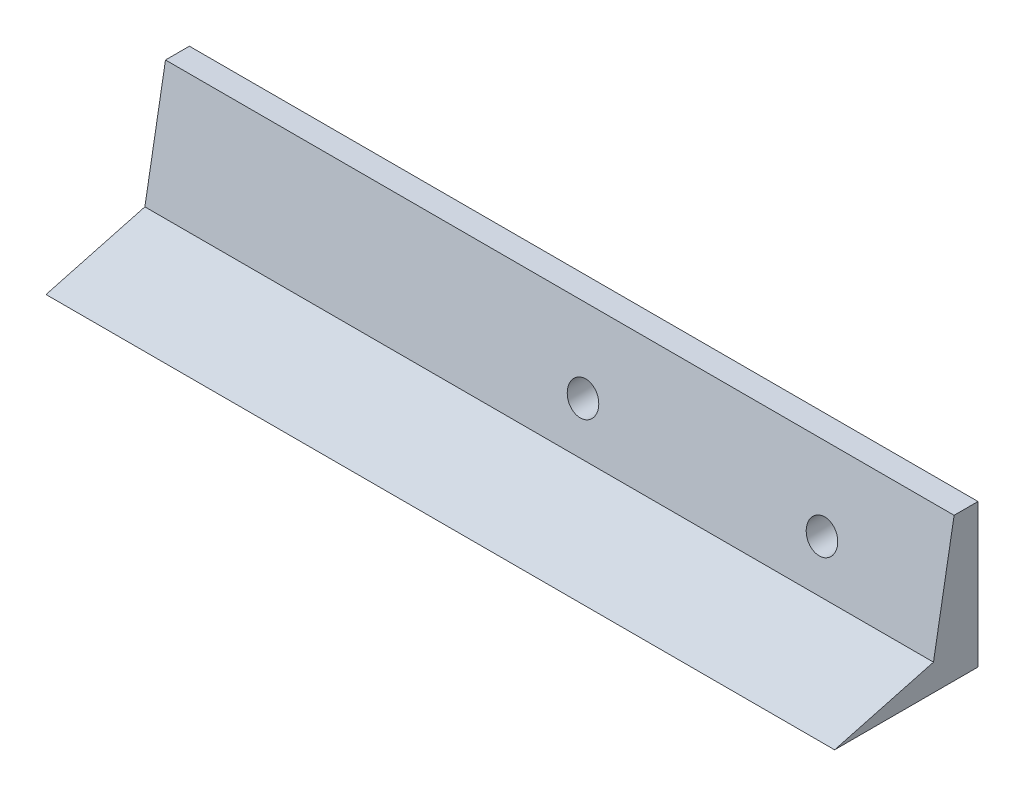
SolidWorks part; units mm, degrees
ref_plane "Front Plane" through (0, 0, 0) normal (0, 0, 1) x (1, 0, 0)
ref_plane "Top Plane" through (0, 0, 0) normal (0, 1, 0) x (1, 0, 0)
ref_plane "Right Plane" through (0, 0, 0) normal (1, 0, 0) x (0, 0, -1)
sketch "Sketch1" plane through (0, 0, 0) normal (1, 0, 0) x (0, 0, -1)
  line L0 (0, 0) -> (0, 30)
  line L3 (-30, 0) -> (0, 0)
  line L4 (-30, 0) -> (-9.3124, 5.5432)
  line L5 (-9.3124, 5.5432) -> (-5, 30)
  line L6 (-5, 30) -> (0, 30)
  dimension "D1" = 30
  dimension "D2" = 30
  dimension "D3" = 10
  dimension "D4" = 15
  dimension "D5" = 5
extrude "Boss-Extrude1" add sketch "Sketch1" along normal blind 100
sketch "Sketch2" plane through (0, 0, 0) normal (0, 0, -1) x (-1, 0, 0)
  line L0 (-100, 15) -> (0, 15) construction
  line L1 (-100, 0) -> (-100, 30) construction
  line L2 (0, 0) -> (0, 30) construction
  line L3 (-100, 30) -> (0, 30) construction
  point P8 (-75, 15)
  point P9 (-25, 15)
  dimension "D1" = 15
  dimension "D2" = 25
  dimension "D3" = 25
hole_wizard "M3 Clearance Hole1" positions "Sketch2" profile "Sketch3" hole size "M3" standard "ANSI Metric" end condition through all
sketch "Sketch3" plane through (25, 15, 0) normal (1, 0, 0) x (0, 1, 0)
  line L0 (0, 0) -> (0, 30)
  line L1 (0, 30) -> (1.7, 30)
  line L2 (1.7, 30) -> (1.7, 0)
  line L5 (1.7, 0) -> (0, 0)
  line L11 (0, -6.35) -> (0, 107.95) construction
  dimension "Thru Hole Dia." = 3.4
  dimension "Thru Hole Depth" = 30
ref_plane "Plane1" through (0, 0, 2.5) normal (0, 0, -1) x (-1, 0, 0)
sketch "Sketch4" plane through (0, 0, 2.5) normal (0, 0, -1) x (-1, 0, 0)
  circle A0 centre (-75, 15) radius 3.25
  circle A1 centre (-25, 15) radius 3.25
  dimension "D1" = 6.5
extrude "Cut-Extrude1" cut sketch "Sketch4" against normal through all
sketch "Sketch6" plane through (0, 0, 0) normal (-1, 0, 0) x (0, 0, 1)
  line L5 (0, 0) -> (30, 0)
  line L6 (30, 0) -> (9.3124, 5.5432)
  line L7 (9.3124, 5.5432) -> (5, 30)
  line L8 (5, 30) -> (0, 30)
  line L9 (0, 30) -> (0, 0)
  line L10 (0, 0) -> (30, 0)
  line L11 (30, 0) -> (9.3124, 5.5432)
  line L12 (9.3124, 5.5432) -> (5, 30)
  line L13 (5, 30) -> (0, 30)
  line L14 (0, 30) -> (0, 0)
  dimension "D1" = 0
extrude "Boss-Extrude2" add sketch "Sketch6" along normal blind 65
